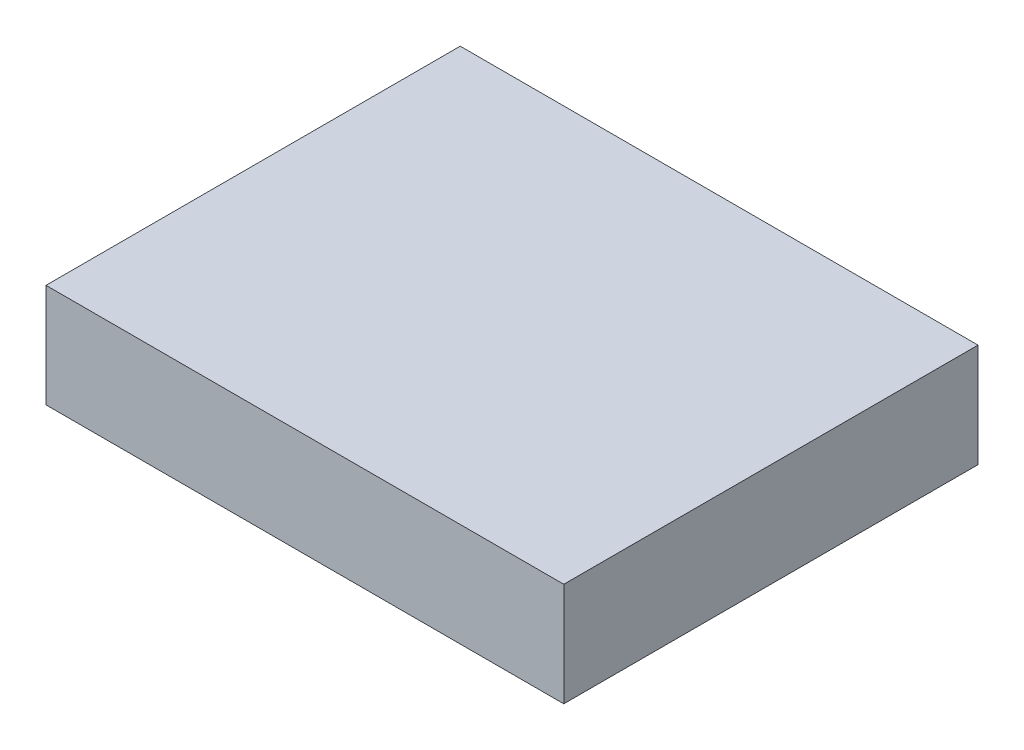
SolidWorks part; units mm, degrees
ref_plane "Front Plane" through (0, 0, 0) normal (0, 0, 1) x (1, 0, 0)
ref_plane "Top Plane" through (0, 0, 0) normal (0, 1, 0) x (1, 0, 0)
ref_plane "Right Plane" through (0, 0, 0) normal (1, 0, 0) x (0, 0, -1)
sketch "Sketch1" plane through (0, 0, 0) normal (0, 0, 1) x (1, 0, 0)
  line L1 (0, 0) -> (25, 0)
  line L2 (0, 0) -> (0, 5)
  line L3 (0, 5) -> (25, 5)
  line L4 (25, 0) -> (25, 5)
extrude "Boss-Extrude1" add sketch "Sketch1" along normal blind 20
